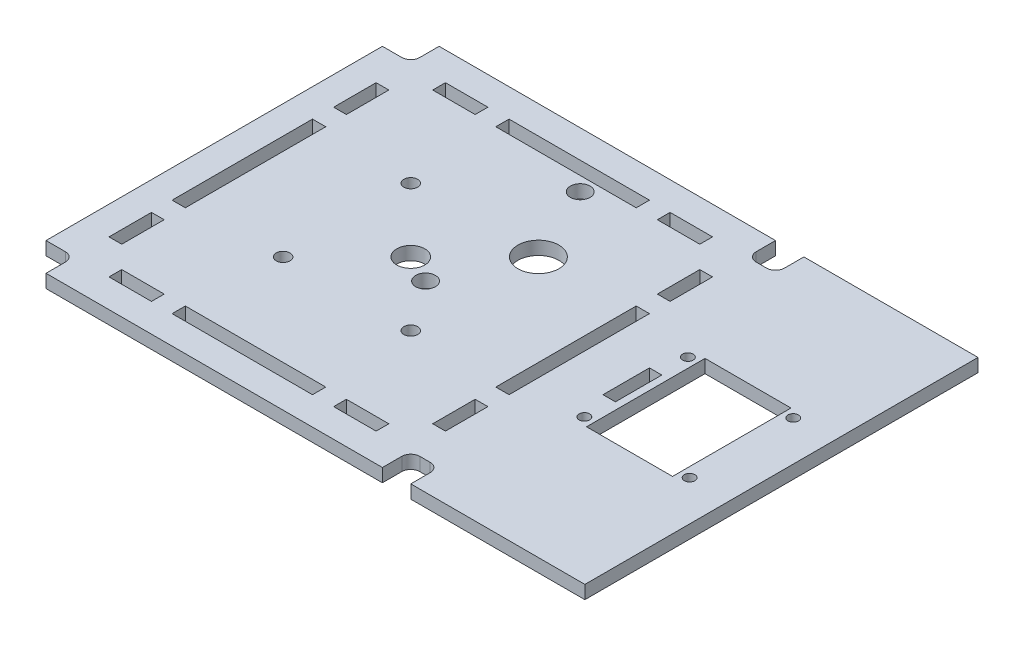
SolidWorks part; units mm, degrees
material "Acrylic (Medium-high impact)"
ref_plane "Front Plane" through (0, 0, 0) normal (0, 0, 1) x (1, 0, 0)
ref_plane "Top Plane" through (0, 0, 0) normal (0, 1, 0) x (1, 0, 0)
ref_plane "Right Plane" through (0, 0, 0) normal (1, 0, 0) x (0, 0, -1)
sketch "스케치2" plane through (0, 0, 0) normal (0, 0, 1) x (1, 0, 0)
  line L0 (44.45, -1.5) -> (46.6794, 0.5074) construction
  line L1 (-44.45, 1.5) -> (44.45, 1.5)
  line L2 (-44.45, 1.5) -> (-44.45, -1.5)
  line L3 (-44.45, -1.5) -> (44.45, -1.5)
  line L4 (44.45, 1.5) -> (44.45, -1.5) construction
  line L5 (-44.45, 1.5) -> (44.45, -1.5) construction
  line L6 (-44.45, -1.5) -> (44.45, 1.5) construction
  line L7 (44.45, -1.5) -> (68.7609, -28.5) construction
  line L8 (46.6794, 0.5074) -> (70.9903, -26.4926) construction
  line L9 (68.7609, -28.5) -> (70.9903, -26.4926) construction
  line L10 (44.45, -1.5) -> (44.45, -28.5) construction
  line L11 (44.45, -28.5) -> (68.7609, -28.5) construction
  line L12 (44.45, 1.5) -> (83.82, 1.5)
  line L13 (83.82, 1.5) -> (83.82, -1.5)
  line L14 (83.82, -1.5) -> (44.45, -1.5)
  arc A0 (44.45, 1.5) -> (46.6794, 0.5074) centre (44.45, -1.5) cw construction
  point P0 (0, 0)
  dimension "D1" = 3
  dimension "D2" = 88.9
  dimension "D3" = 48
  dimension "D4" = 3
  dimension "D5" = 39.37
  dimension "30mm" = 30
extrude "보스-돌출1" add sketch "스케치2" along normal blind 88.9 contours A0 L1 L2 L3 L7 L9 L8
sketch "스케치4" plane through (0, 1.5, 0) normal (0, 1, 0) x (1, 0, 0)
  line L0 (-44.45, -88.9) -> (-44.45, 0) construction
  line L1 (-44.45, -88.9) -> (44.45, -88.9) construction
  line L2 (-44.45, -88.9) -> (-44.45, 0) construction
  line L3 (-44.45, 0) -> (44.45, 0) construction
  line L4 (44.45, -88.9) -> (44.45, 0) construction
  line L5 (-44.45, -88.9) -> (44.45, 0) construction
  line L6 (-44.45, 0) -> (44.45, -88.9) construction
  line L7 (-44.45, 0) -> (83.82, 0) construction
  line L8 (-38.1, -82.55) -> (-44.45, -88.9) construction
  line L9 (-38.1, -82.55) -> (38.1, -82.55) construction
  line L10 (-38.1, -82.55) -> (-38.1, -6.35) construction
  line L11 (-38.1, -6.35) -> (38.1, -6.35) construction
  line L12 (38.1, -82.55) -> (38.1, -6.35) construction
  line L13 (-38.1, -82.55) -> (38.1, -6.35) construction
  line L14 (-38.1, -6.35) -> (38.1, -82.55) construction
  line L15 (44.45, 0) -> (38.1, -6.35) construction
  line L16 (0, -44.45) -> (0, -81.05) construction
  line L17 (-15.875, -79.55) -> (15.875, -79.55)
  line L18 (-15.875, -79.55) -> (-15.875, -82.55)
  line L19 (-15.875, -82.55) -> (15.875, -82.55)
  line L20 (15.875, -79.55) -> (15.875, -82.55)
  line L21 (-15.875, -79.55) -> (15.875, -82.55) construction
  line L22 (-15.875, -82.55) -> (15.875, -79.55) construction
  line L23 (-35.1, -28.575) -> (-38.1, -28.575)
  line L24 (-35.1, -28.575) -> (-35.1, -60.325)
  line L25 (-35.1, -60.325) -> (-38.1, -60.325)
  line L26 (-38.1, -28.575) -> (-38.1, -60.325)
  line L27 (15.875, -9.35) -> (15.875, -6.35)
  line L28 (15.875, -9.35) -> (-15.875, -9.35)
  line L29 (-15.875, -9.35) -> (-15.875, -6.35)
  line L30 (15.875, -6.35) -> (-15.875, -6.35)
  line L31 (35.1, -60.325) -> (38.1, -60.325)
  line L32 (35.1, -60.325) -> (35.1, -28.575)
  line L33 (35.1, -28.575) -> (38.1, -28.575)
  line L34 (38.1, -60.325) -> (38.1, -28.575)
  line L35 (0, -9.35) -> (0, -44.45) construction
  line L36 (-35.1, -44.45) -> (0, -44.45) construction
  line L37 (0, -44.45) -> (0, -9.35) construction
  line L38 (0, -44.45) -> (35.1, -44.45) construction
  circle A0 centre (-41.275, -85.725) radius 1.5
  circle A1 centre (-41.275, -3.175) radius 1.5
  circle A2 centre (41.275, -3.175) radius 1.5
  circle A3 centre (41.275, -85.725) radius 1.5
  point P0 (0, -44.45)
  point P13 (0, -44.45)
  point P19 (0, -81.05)
  point P27 (0, -44.45)
  point P47 (0, -44.45)
  dimension "D3" = 3
  dimension "D1" = 76.2
  dimension "D2" = 76.2
  dimension "D5" = 3
  dimension "D6" = 31.75
  dimension "D8" = 35.1
  dimension "D4" = 4
extrude "컷-돌출1" cut sketch "스케치4" against normal up to surface (3 mm away) up to face at (19.685, -1.5, 44.45)
sketch "스케치5" plane through (0, 1.5, 0) normal (0, 1, 0) x (1, 0, 0)
  line L0 (0, 0) -> (0, -88.9) construction
  line L1 (-44.45, -88.9) -> (83.82, -88.9) construction
  line L2 (-44.45, -44.45) -> (44.45, -44.45) construction
  line L3 (-44.45, -88.9) -> (-44.45, 0) construction
  line L4 (44.45, -88.9) -> (44.45, 0) construction
  circle A0 centre (-14.4318, -30.0182) radius 15.875 construction
  circle A1 centre (-14.4318, -30.0182) radius 12.827 construction
  circle A2 centre (-14.4318, -30.0182) radius 1.56
  circle A3 centre (14.4318, -30.0182) radius 12.827 construction
  circle A4 centre (14.4318, -30.0182) radius 15.875 construction
  circle A5 centre (14.4318, -30.0182) radius 1.56
  circle A6 centre (14.4318, -58.8818) radius 12.827 construction
  circle A7 centre (14.4318, -58.8818) radius 15.875 construction
  circle A8 centre (14.4318, -58.8818) radius 1.56
  circle A9 centre (-14.4318, -58.8818) radius 12.827 construction
  circle A10 centre (-14.4318, -58.8818) radius 15.875 construction
  circle A11 centre (-14.4318, -58.8818) radius 1.56
  point P8 (0, -44.45)
  point P9 (-14.4318, -30.0182)
  point P10 (-1.6048, -30.0182)
  point P14 (-14.4318, -42.8452)
  point P34 (0, -44.45)
  dimension "D1" = 31.75
  dimension "D2" = 25.654
  dimension "D5" = 3.12
  dimension "D3" = 28.8636
  dimension "D4" = 28.8636
  dimension "D6" = 4
extrude "컷-돌출2" cut sketch "스케치5" against normal up to surface (3 mm away) up to face at (0, -1.5, 81.05)
sketch "스케치7" plane through (0, 1.5, 0) normal (0, 1, 0) x (1, 0, 0)
  line L0 (22.4618, -12.5282) -> (22.4618, -47.5082) construction
  line L1 (14.4318, -30.0182) -> (22.4618, -30.0182) construction
  line L2 (14.4318, -30.0182) -> (14.4318, -9.35) construction
  line L3 (-15.875, -9.35) -> (15.875, -9.35) construction
  circle A0 centre (14.4318, -30.0182) radius 4.635
  circle A1 centre (22.4618, -12.5282) radius 2.23 construction
  circle A2 centre (22.4618, -47.5082) radius 2.23 construction
  circle A3 centre (14.4318, -30.0182) radius 1.56 construction
  circle A4 centre (22.4618, -30.0182) radius 14.045 construction
  circle A6 centre (14.4318, -30.0182) radius 15.875 construction
  circle A7 centre (14.4318, -58.8818) radius 15.875 construction
  circle A8 centre (6.4018, -47.5082) radius 2.23
  circle A9 centre (6.4018, -12.5282) radius 2.23
  point P7 (9.7968, -30.0182)
  point P8 (8.4168, -30.0182)
  dimension "D1" = 9.27
  dimension "D2" = 4.46
  dimension "D4" = 28.09
  dimension "D6" = 31.75
  dimension "D3" = 34.98
  dimension "D5" = 1.38
extrude "컷-돌출3" cut sketch "스케치7" against normal up to surface (3 mm away) up to face at (-12.8718, -1.5, 58.8818)
sketch "스케치8" plane through (0, 1.5, 0) normal (0, 1, 0) x (1, 0, 0)
  line L0 (-44.45, -88.9) -> (83.82, -88.9) construction
  line L1 (-30.2, -9.35) -> (-20.6, -9.35) construction
  line L2 (-30.2, -9.35) -> (-30.2, -6.35) construction
  line L3 (-30.2, -6.35) -> (-20.6, -6.35) construction
  line L4 (-20.6, -9.35) -> (-20.6, -6.35) construction
  line L5 (-30.2, -9.35) -> (-20.6, -6.35) construction
  line L6 (-30.2, -6.35) -> (-20.6, -9.35) construction
  line L7 (44.45, -88.9) -> (-44.45, -88.9) construction
  line L8 (44.45, -88.9) -> (44.45, 0) construction
  line L9 (44.45, 0) -> (-44.45, 0) construction
  line L10 (-44.45, -88.9) -> (-44.45, 0) construction
  line L11 (44.45, -88.9) -> (-44.45, 0) construction
  line L12 (44.45, 0) -> (-44.45, -88.9) construction
  line L13 (44.45, -88.9) -> (44.45, 0) construction
  line L14 (-38.1, -28.575) -> (-38.1, -6.35) construction
  line L15 (-38.1, -6.35) -> (38.1, -6.35) construction
  line L16 (0, -44.45) -> (0, -6.35) construction
  line L17 (-30.2, -9.29) -> (-20.6, -9.29)
  line L18 (-30.2, -9.29) -> (-30.2, -6.41)
  line L19 (-30.2, -6.41) -> (-20.6, -6.41)
  line L20 (-20.6, -9.29) -> (-20.6, -6.41)
  line L21 (-30.2, -9.29) -> (-20.6, -6.41) construction
  line L22 (-30.2, -6.41) -> (-20.6, -9.29) construction
  line L23 (-35.1, -14.25) -> (-38.1, -14.25) construction
  line L24 (-35.1, -14.25) -> (-35.1, -23.85) construction
  line L25 (-35.1, -23.85) -> (-38.1, -23.85) construction
  line L26 (-38.1, -14.25) -> (-38.1, -23.85) construction
  line L27 (-35.1, -14.25) -> (-38.1, -23.85) construction
  line L28 (-35.1, -23.85) -> (-38.1, -14.25) construction
  line L29 (-38.04, -23.85) -> (-35.16, -23.85)
  line L30 (-38.04, -23.85) -> (-38.04, -14.25)
  line L31 (-38.04, -14.25) -> (-35.16, -14.25)
  line L32 (-35.16, -23.85) -> (-35.16, -14.25)
  line L33 (-38.04, -23.85) -> (-35.16, -14.25) construction
  line L34 (-38.04, -14.25) -> (-35.16, -23.85) construction
  line L35 (0, -44.45) -> (44.45, -44.45) construction
  line L36 (38.04, -23.85) -> (35.16, -23.85)
  line L37 (35.16, -23.85) -> (35.16, -14.25)
  line L38 (38.04, -23.85) -> (38.04, -14.25)
  line L39 (38.04, -14.25) -> (35.16, -14.25)
  line L40 (20.6, -9.29) -> (20.6, -6.41)
  line L41 (30.2, -6.41) -> (20.6, -6.41)
  line L42 (30.2, -9.29) -> (20.6, -9.29)
  line L43 (30.2, -9.29) -> (30.2, -6.41)
  line L44 (38.04, -65.05) -> (35.16, -65.05)
  line L45 (38.04, -65.05) -> (38.04, -74.65)
  line L46 (38.04, -74.65) -> (35.16, -74.65)
  line L47 (35.16, -65.05) -> (35.16, -74.65)
  line L48 (20.6, -79.61) -> (20.6, -82.49)
  line L49 (30.2, -79.61) -> (20.6, -79.61)
  line L50 (30.2, -82.49) -> (20.6, -82.49)
  line L51 (30.2, -79.61) -> (30.2, -82.49)
  line L52 (-30.2, -79.61) -> (-20.6, -79.61)
  line L53 (-30.2, -82.49) -> (-20.6, -82.49)
  line L54 (-30.2, -79.61) -> (-30.2, -82.49)
  line L55 (-20.6, -79.61) -> (-20.6, -82.49)
  line L56 (-38.04, -65.05) -> (-35.16, -65.05)
  line L57 (-38.04, -74.65) -> (-35.16, -74.65)
  line L58 (-38.04, -65.05) -> (-38.04, -74.65)
  line L59 (-35.16, -65.05) -> (-35.16, -74.65)
  point P0 (-25.4, -7.85)
  point P5 (0, -44.45)
  point P18 (-36.6, -19.05)
  point P20 (-25.4, -7.85)
  point P29 (-36.6, -19.05)
  dimension "D1" = 3
  dimension "D2" = 25.4
  dimension "D3" = 2.88
  dimension "D4" = 9.6
  dimension "D5" = 3
  dimension "D6" = 9.6
  dimension "D7" = 25.4
  dimension "D8" = 2.88
extrude "컷-돌출4" cut sketch "스케치8" against normal up to surface (3 mm away) up to face at (19.0668, -1.5, 30.0182)
sketch "스케치9" plane through (0, 1.5, 0) normal (0, 1, 0) x (1, 0, 0)
  line L1 (44.45, -88.9) -> (-44.45, -88.9) construction
  line L2 (44.45, -88.9) -> (44.45, 0) construction
  line L3 (44.45, 0) -> (-44.45, 0) construction
  line L4 (-44.45, -88.9) -> (-44.45, 0) construction
  line L5 (44.45, -88.9) -> (-44.45, 0) construction
  line L6 (44.45, 0) -> (-44.45, -88.9) construction
  circle A0 centre (0, -44.45) radius 3.175
  point P0 (0, -44.45)
  dimension "D1" = 6.35
extrude "컷-돌출5" cut sketch "스케치9" against normal up to surface (3 mm away) up to face at (36.6, -1.5, 69.85)
sketch "스케치12" plane through (0, 1.5, 0) normal (0, 1, 0) x (1, 0, 0)
  line L1 (-41.275, -82.5496) -> (-44.025, -84.1373)
  line L2 (-44.025, -84.1373) -> (-44.025, -87.3127)
  line L3 (-44.025, -87.3127) -> (-41.275, -88.9004)
  line L4 (-41.275, -88.9004) -> (-38.525, -87.3127)
  line L5 (-38.525, -87.3127) -> (-38.525, -84.1373)
  line L6 (-38.525, -84.1373) -> (-41.275, -82.5496)
  circle A0 centre (-41.275, -85.725) radius 2.75
  circle A1 centre (-41.275, -85.725) radius 1.5 construction
  circle A2 centre (-41.275, -85.725) radius 2.75 construction
  dimension "D1" = 5.5
sketch "스케치13" plane through (0, 1.5, 0) normal (0, 1, 0) x (1, 0, 0)
  line L0 (-38.04, -74.65) -> (-38.04, -82.49) construction
  line L1 (-44.45, -88.9) -> (-38.0365, -88.9)
  line L2 (-44.45, -88.9) -> (-44.45, -82.4865)
  line L3 (-44.45, -82.4865) -> (-38.0365, -82.4865)
  line L4 (-38.0365, -88.9) -> (-38.0365, -82.4865)
  line L5 (-44.45, -88.9) -> (-38.0365, -82.4865) construction
  line L6 (-44.45, -82.4865) -> (-38.0365, -88.9) construction
  line L7 (-38.04, -82.49) -> (-30.2, -82.49) construction
  line L8 (-44.45, 0) -> (-38.0365, 0)
  line L9 (-44.45, 0) -> (-44.45, -6.4135)
  line L10 (-44.45, -6.4135) -> (-38.0365, -6.4135)
  line L11 (-38.0365, 0) -> (-38.0365, -6.4135)
  line L12 (44.45, 0) -> (44.45, -6.4135)
  line L13 (44.45, 0) -> (38.0365, 0)
  line L14 (38.0365, 0) -> (38.0365, -6.4135)
  line L15 (44.45, -6.4135) -> (38.0365, -6.4135)
  line L16 (44.45, -88.9) -> (38.0365, -88.9)
  line L17 (44.45, -88.9) -> (44.45, -82.4865)
  line L18 (44.45, -82.4865) -> (38.0365, -82.4865)
  line L19 (38.0365, -88.9) -> (38.0365, -82.4865)
  point P4 (-41.2432, -85.6932)
  point P14 (0, -44.45)
  point P28 (0, -44.45)
  dimension "D1" = 6.4135
  dimension "D2" = 4
extrude "컷-돌출7" cut sketch "스케치13" against normal blind 5.08
sketch "스케치14" plane through (0, 1.5, 0) normal (0, 1, 0) x (1, 0, 0)
  circle A0 centre (-41.275, -85.725) radius 3.1754 construction
fillet "필렛2" radius 2.032 6 edges at (38.0365, 0, 6.4135) (44.45, 0, 6.4135) (-38.0365, 0, 6.4135) (44.45, 0, 82.4865) (38.0365, 0, 82.4865) (-38.0365, 0, 82.4865)
sketch "스케치18" plane through (0, 1.5, 0) normal (0, 1, 0) x (1, 0, 0)
  line L0 (25.0731, 51.4127) -> (25.0731, 30.4766) construction
  line L1 (11.3809, 37.522) -> (38.7652, 37.522) construction
  line L2 (11.3809, 37.522) -> (11.3809, 65.3033) construction
  line L3 (11.3809, 65.3033) -> (38.7652, 65.3033) construction
  line L4 (38.7652, 37.522) -> (38.7652, 65.3033) construction
  line L5 (11.3809, 37.522) -> (38.7652, 65.3033) construction
  line L6 (11.3809, 65.3033) -> (38.7652, 37.522) construction
  line L7 (69.5231, 50.1427) -> (-19.3769, 50.1427) construction
  line L8 (25.0731, 51.4127) -> (38.4676, 51.4127) construction
  line L9 (11.3809, 63.3189) -> (13.3652, 63.3189) construction
  line L10 (11.6785, 61.1361) -> (38.4676, 61.1361) construction
  line L11 (11.6785, 61.1361) -> (11.6785, 41.6892) construction
  line L12 (11.6785, 41.6892) -> (38.4676, 41.6892) construction
  line L13 (38.4676, 61.1361) -> (38.4676, 41.6892) construction
  line L14 (11.6785, 61.1361) -> (38.4676, 41.6892) construction
  line L15 (11.6785, 41.6892) -> (38.4676, 61.1361) construction
  line L16 (13.3652, 63.3189) -> (13.3652, 65.3033) construction
  line L17 (64.135, -88.9) -> (64.135, 0) construction
  line L18 (44.45, -88.9) -> (83.82, -88.9) construction
  line L19 (44.45, 0) -> (83.82, 0) construction
  line L20 (62.865, -44.45) -> (64.135, -44.45) construction
  line L21 (72.5884, -57.8445) -> (53.1416, -57.8445)
  line L22 (72.5884, -57.8445) -> (72.5884, -31.0555)
  line L23 (72.5884, -31.0555) -> (53.1416, -31.0555)
  line L24 (53.1416, -57.8445) -> (53.1416, -31.0555)
  line L25 (72.5884, -57.8445) -> (53.1416, -31.0555) construction
  line L26 (72.5884, -31.0555) -> (53.1416, -57.8445) construction
  line L27 (50.9588, -56.1578) -> (48.9744, -56.1578) construction
  line L28 (76.7556, -30.7578) -> (48.9744, -30.7578) construction
  line L29 (76.7556, -30.7578) -> (76.7556, -58.1422) construction
  line L30 (76.7556, -58.1422) -> (48.9744, -58.1422) construction
  line L31 (48.9744, -30.7578) -> (48.9744, -58.1422) construction
  line L32 (76.7556, -30.7578) -> (48.9744, -58.1422) construction
  line L33 (76.7556, -58.1422) -> (48.9744, -30.7578) construction
  line L34 (50.9588, -56.1578) -> (50.9588, -58.1422) construction
  line L35 (50.9588, -32.7422) -> (48.9744, -32.7422) construction
  line L36 (50.9588, -32.7422) -> (50.9588, -30.7578) construction
  line L37 (62.865, -44.45) -> (62.865, -57.8445) construction
  circle A0 centre (13.3652, 63.3189) radius 1.1906 construction
  circle A1 centre (13.3652, 63.3189) radius 1.8852 construction
  circle A2 centre (36.7809, 63.3189) radius 1.1906 construction
  circle A3 centre (36.7809, 39.5064) radius 1.1906 construction
  circle A4 centre (13.3652, 39.5064) radius 1.1906 construction
  circle A5 centre (50.9588, -56.1578) radius 1.1906
  circle A6 centre (50.9588, -32.7422) radius 1.1906
  circle A9 centre (74.7713, -32.7422) radius 1.1906
  circle A10 centre (74.7713, -56.1578) radius 1.1906
  point P0 (25.0731, 51.4127)
  point P31 (62.865, -44.45)
  dimension "D6" = 2.3813
  dimension "D7" = 3.7703
  dimension "D1" = 27.3844
  dimension "D2" = 27.7812
  dimension "D3" = 26.7891
  dimension "D4" = 19.4469
  dimension "D5" = 1.9844
  dimension "D8" = 1.27
  dimension "D9" = 1.27
extrude "컷-돌출8" cut sketch "스케치18" against normal up to surface (3 mm away) up to face at (15.5553, -1.5, 44.45)
sketch "스케치19" plane through (0, 1.5, 0) normal (0, 1, 0) x (1, 0, 0)
  line L0 (50.1224, -44.45) -> (53.1416, -44.45) construction
  line L1 (48.7204, -49.7) -> (51.5244, -49.7)
  line L2 (48.7204, -49.7) -> (48.7204, -39.2)
  line L3 (48.7204, -39.2) -> (51.5244, -39.2)
  line L4 (51.5244, -49.7) -> (51.5244, -39.2)
  line L5 (48.7204, -49.7) -> (51.5244, -39.2) construction
  line L6 (48.7204, -39.2) -> (51.5244, -49.7) construction
  line L7 (53.1416, -31.0555) -> (53.1416, -57.8445) construction
  line L9 (48.9744, -30.7578) -> (48.9744, -58.1422) construction
  point P0 (50.1224, -44.45)
  point P9 (50.0572, -44.45)
  dimension "D1" = 2.55
  dimension "D2" = 10.5
  dimension "D3" = 0.254
extrude "컷-돌출9" cut sketch "스케치19" against normal blind 2000
